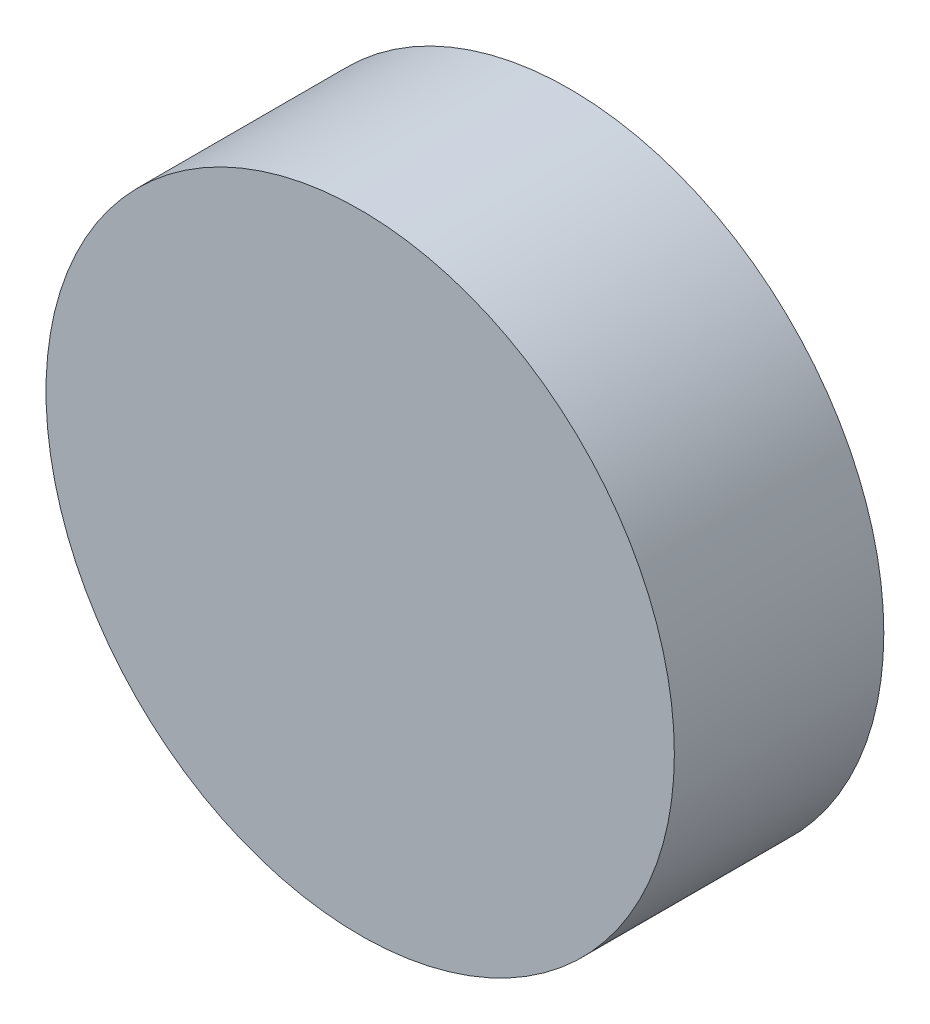
SolidWorks part; units mm, degrees
material "wheel"
ref_plane "前视基准面" through (0, 0, 0) normal (0, 0, 1) x (1, 0, 0)
ref_plane "上视基准面" through (0, 0, 0) normal (0, 1, 0) x (1, 0, 0)
ref_plane "右视基准面" through (0, 0, 0) normal (1, 0, 0) x (0, 0, -1)
other "Configuration Table"
sketch "草图1" plane through (0, 0, 0) normal (0, 0, 1) x (1, 0, 0)
  circle A0 centre (0, 0) radius 75
  dimension "D1" = 150
extrude "凸台-拉伸1" add sketch "草图1" along normal blind 50
